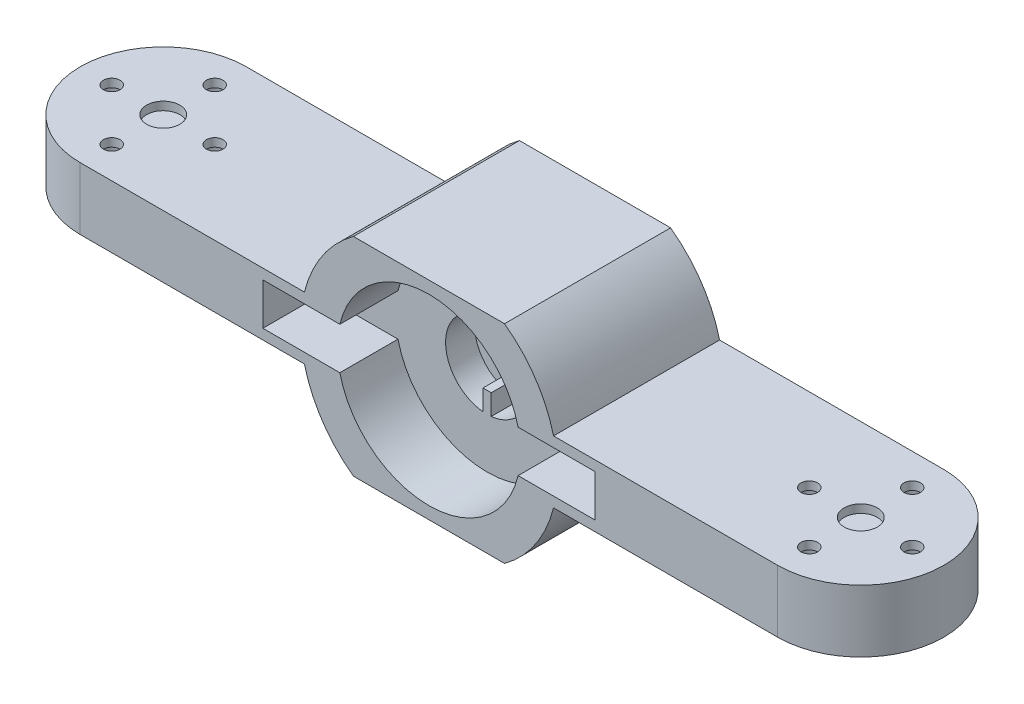
SolidWorks part; units mm, degrees
material "6061 Alloy"
ref_plane "Front Plane" through (0, 0, 0) normal (0, 0, 1) x (1, 0, 0)
ref_plane "Top Plane" through (0, 0, 0) normal (0, 1, 0) x (1, 0, 0)
ref_plane "Right Plane" through (0, 0, 0) normal (1, 0, 0) x (0, 0, -1)
sketch "Sketch1" plane through (0, 0, 0) normal (0, 1, 0) x (1, 0, 0)
  line L1 (-42, -10) -> (42, -10)
  line L3 (-42, 10) -> (42, 10)
  line L5 (-42, -10) -> (42, 10) construction
  line L6 (-42, 10) -> (42, -10) construction
  arc A0 (-42, 10) -> (-42, -10) centre (-42, 0) ccw
  arc A1 (42, -10) -> (42, 10) centre (42, 0) ccw
  point P0 (0, 0)
  point P7 (52, 0)
  dimension "D3" = 10
  dimension "D1" = 84
  dimension "D2" = 20
  dimension "D4" = 10
extrude "Boss-Extrude1" add sketch "Sketch1" along normal blind 25
sketch "Sketch2" plane through (0, 0, 10) normal (0, 0, 1) x (1, 0, 0)
  line L0 (0, 0) -> (0, 12.5) construction
  circle A0 centre (0, 12.5) radius 11.025
  dimension "D2" = 22.05
  dimension "D1" = 12.5
extrude "Cut-Extrude1" cut sketch "Sketch2" against normal blind 7
sketch "Sketch3" plane through (0, 0, 0) normal (0, -1, 0) x (1, 0, 0)
  line L0 (-42, 10) -> (42, 10) construction
  line L2 (15, -10) -> (15, 10)
  line L4 (-15, -10) -> (-15, 10)
  line L5 (15, -10) -> (-15, 10) construction
  line L6 (15, 10) -> (-15, -10) construction
  line L7 (-15, 10) -> (-42, 10)
  line L8 (-42, -10) -> (-15, -10)
  line L9 (15, 10) -> (42, 10)
  line L10 (15, -10) -> (42, -10)
  arc A0 (-42, 10) -> (-42, -10) centre (-42, 0) ccw
  arc A1 (42, -10) -> (42, 10) centre (42, 0) ccw
  point P7 (0, 0)
extrude "Cut-Extrude3" cut sketch "Sketch3" against normal blind 8.75
sketch "Sketch4" plane through (0, 25, 0) normal (0, 1, 0) x (1, 0, 0)
  line L0 (15, -10) -> (15, 10)
  line L1 (-15, -10) -> (-15, 10)
  line L2 (15, -10) -> (-15, 10) construction
  line L3 (15, 10) -> (-15, -10) construction
  line L4 (-15, 10) -> (-55, 10)
  line L5 (-55, -10) -> (-15, -10)
  line L6 (15, 10) -> (55, 10)
  line L7 (15, -10) -> (55, -10)
  arc A0 (-55, 10) -> (-55, -10) centre (-55, 0) ccw
  arc A1 (55, -10) -> (55, 10) centre (55, 0) ccw
  point P2 (0, 0)
  dimension "D1" = 0
  dimension "D2" = 0
extrude "Cut-Extrude5" cut sketch "Sketch4" against normal blind 8.75
sketch "Sketch5" plane through (0, 16.25, 0) normal (0, 1, 0) x (1, 0, 0)
  line L0 (0, 0) -> (-42, 0) construction
  line L1 (-42, 0) -> (-35.8, 0) construction
  line L2 (-42, 0) -> (-42, 6.2) construction
  line L3 (-42, 0) -> (-48.2, 0) construction
  line L4 (-42, 0) -> (-42, -6.2) construction
  line L5 (0, 0) -> (42, 0) construction
  line L6 (42, 0) -> (48.2, 0) construction
  line L7 (42, 0) -> (42, 6.2) construction
  line L8 (42, 0) -> (35.8, 0) construction
  line L9 (42, 0) -> (42, -6.2) construction
  circle A0 centre (-42, 6.2) radius 1
  circle A1 centre (-35.8, 0) radius 1
  circle A2 centre (-42, -6.2) radius 1
  circle A3 centre (-48.2, 0) radius 1
  circle A4 centre (42, 6.2) radius 1
  circle A5 centre (48.2, 0) radius 1
  circle A6 centre (42, -6.2) radius 1
  circle A7 centre (35.8, 0) radius 1
  dimension "D3" = 2
  dimension "D4" = 2
  dimension "D5" = 2
  dimension "D6" = 2
  dimension "D13" = 2
  dimension "D14" = 2
  dimension "D15" = 2
  dimension "D16" = 2
  dimension "D1" = 6.2
  dimension "D2" = 6.2
  dimension "D7" = 6.2
  dimension "D8" = 6.2
  dimension "D9" = 0
  dimension "D10" = 0
  dimension "D11" = 6.2
  dimension "D12" = 6.2
  dimension "D17" = 6.2
  dimension "D18" = 6.2
  dimension "D19" = 0
  dimension "D20" = 0
extrude "Cut-Extrude6" cut sketch "Sketch5" against normal blind 7.5
sketch "Sketch6" plane through (0, 8.75, 0) normal (0, -1, 0) x (1, 0, 0)
  line L0 (0, 0) -> (-42, 0) construction
  line L1 (-42, 0) -> (-35.8, 0) construction
  line L2 (-42, 0) -> (-48.2, 0) construction
  line L3 (-42, 0) -> (-42, 6.2) construction
  line L4 (-42, 0) -> (-42, -6.2) construction
  line L5 (-48.2, 0) -> (-35.8, 0) construction
  line L6 (0, 0) -> (42, 0) construction
  line L7 (42, 0) -> (48.2, 0) construction
  line L8 (42, 0) -> (35.8, 0) construction
  line L9 (42, 0) -> (42, 6.2) construction
  line L10 (42, 0) -> (42, -6.2) construction
  line L11 (35.8, 0) -> (48.2, 0) construction
  circle A0 centre (-42, 6.2) radius 1.95
  circle A1 centre (-35.8, 0) radius 1.95
  circle A2 centre (-48.2, 0) radius 1.95
  circle A3 centre (-42, -6.2) radius 1.95
  circle A4 centre (42, 6.2) radius 1.95
  circle A5 centre (48.2, 0) radius 1.95
  circle A6 centre (35.8, 0) radius 1.95
  circle A7 centre (42, -6.2) radius 1.95
  dimension "D5" = 3.9
  dimension "D6" = 3.9
  dimension "D7" = 3.9
  dimension "D8" = 3.9
  dimension "D15" = 3.9
  dimension "D16" = 3.9
  dimension "D17" = 3.9
  dimension "D18" = 3.9
  dimension "D1" = 6.2
  dimension "D2" = 6.2
  dimension "D3" = 6.2
  dimension "D4" = 6.2
  dimension "D9" = 0
  dimension "D10" = 0
  dimension "D11" = 6.2
  dimension "D12" = 6.2
  dimension "D13" = 6.2
  dimension "D14" = 6.2
  dimension "D19" = 0
  dimension "D20" = 0
  dimension "D21" = 42
extrude "Cut-Extrude7" cut sketch "Sketch6" against normal offset from surface (6.5 mm away) 1 up to face at (-42, 16.25, -5.2)
sketch "Sketch7" plane through (0, 16.25, 0) normal (0, 1, 0) x (1, 0, 0)
  line L0 (0, 0) -> (-42, 0) construction
  line L1 (0, 0) -> (42, 0) construction
  circle A0 centre (-42, 0) radius 2
  circle A1 centre (42, 0) radius 2
  dimension "D1" = 4
  dimension "D2" = 4
extrude "Cut-Extrude8" cut sketch "Sketch7" against normal blind 1
sketch "Sketch8" plane through (0, 0, 10) normal (0, 0, 1) x (1, 0, 0)
  line L0 (0, 0) -> (0, 12.5) construction
  line L1 (-15, 16.25) -> (-15, 25)
  line L2 (15, 0) -> (9.1001, 0)
  line L3 (15, 0) -> (15, 8.75)
  line L4 (15, 25) -> (9.1001, 25)
  line L5 (-15, 0) -> (-15, 8.75)
  line L6 (15, 0) -> (-15, 25) construction
  line L7 (15, 25) -> (-15, 0) construction
  line L8 (-9.1001, 25) -> (-15, 25)
  line L9 (15, 16.25) -> (15, 25)
  line L10 (-9.1001, 0) -> (-15, 0)
  arc A0 (-15, 8.75) -> (-9.1001, 0) centre (0, 12.5) ccw
  arc A1 (-9.1001, 25) -> (-15, 16.25) centre (0, 12.5) ccw
  arc A2 (15, 16.25) -> (9.1001, 25) centre (0, 12.5) ccw
  arc A3 (9.1001, 0) -> (15, 8.75) centre (0, 12.5) ccw
  dimension "D1" = 12.5
extrude "Cut-Extrude9" cut sketch "Sketch8" against normal through all
sketch "Sketch9" plane through (0, 0, 3) normal (0, 0, 1) x (1, 0, 0)
  line L0 (0, 0) -> (0, 12.5) construction
  line L2 (-0.5, 10) -> (0.5, 10)
  line L4 (-0.5, 15) -> (0.5, 15)
  line L6 (-0.5, 10) -> (0.5, 15) construction
  line L7 (-0.5, 15) -> (0.5, 10) construction
  line L8 (0.5, 15) -> (-0.5, 15)
  line L9 (0.5, 15) -> (0.5, 17.4749)
  line L11 (-0.5, 15) -> (-0.5, 17.4749)
  line L12 (0.5, 10) -> (-0.5, 10)
  line L13 (0.5, 10) -> (0.5, 7.5251)
  line L15 (-0.5, 10) -> (-0.5, 7.5251)
  arc A0 (-0.5, 17.4749) -> (-0.5, 7.5251) centre (0, 12.5) ccw
  arc A1 (0.5, 7.5251) -> (0.5, 17.4749) centre (0, 12.5) ccw
  dimension "D1" = 5
  dimension "D3" = 10
  dimension "D2" = 1
  dimension "D4" = 1
  dimension "D5" = 2.4749
extrude "Cut-Extrude10" cut sketch "Sketch9" against normal blind 3.5 contours L13 A1 L9 L4 L11 A0 L15 L2
sketch "Sketch10" plane through (0, 0, 10) normal (0, 0, 1) x (1, 0, 0)
  line L1 (-20, 15.025) -> (20, 15.025)
  line L2 (-20, 15.025) -> (-20, 9.975)
  line L3 (-20, 9.975) -> (20, 9.975)
  line L4 (20, 15.025) -> (20, 9.975)
  line L5 (-20, 15.025) -> (20, 9.975) construction
  line L6 (-20, 9.975) -> (20, 15.025) construction
  point P0 (0, 12.5)
  dimension "D1" = 5.05
  dimension "D2" = 40
extrude "Cut-Extrude11" cut sketch "Sketch10" against normal blind 7
